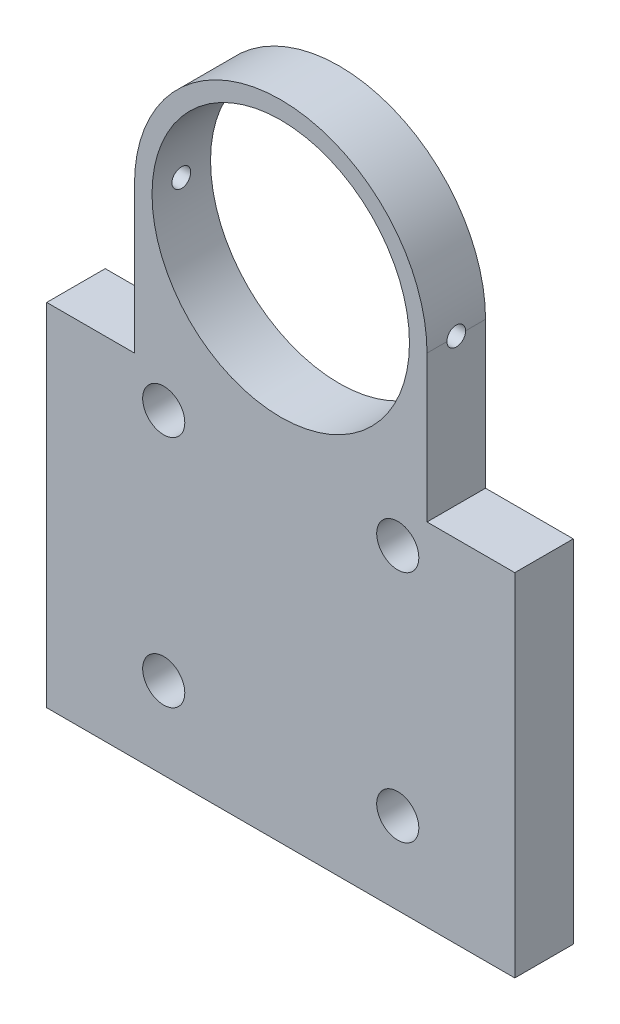
SolidWorks part; units mm, degrees
ref_plane "Plan de face" through (0, 0, 0) normal (0, 0, 1) x (1, 0, 0)
ref_plane "Plan de dessus" through (0, 0, 0) normal (0, 1, 0) x (1, 0, 0)
ref_plane "Plan de droite" through (0, 0, 0) normal (1, 0, 0) x (0, 0, -1)
sketch "Esquisse1" plane through (0, 0, 0) normal (0, 0, 1) x (1, 0, 0)
  line L1 (-21, 10.5789) -> (19, 10.5789)
  line L2 (-21, 10.5789) -> (-21, -19.4211)
  line L3 (-21, -19.4211) -> (19, -19.4211)
  line L4 (19, 10.5789) -> (19, -19.4211)
  dimension "D1" = 30
  dimension "D2" = 40
extrude "Boss.-Extru.1" add sketch "Esquisse1" along normal blind 5
sketch "Esquisse2" plane through (0, 0, 5) normal (0, 0, 1) x (1, 0, 0)
  line L0 (-1, 10.5789) -> (-1, 23.0789) construction
  line L1 (19, 10.5789) -> (-21, 10.5789) construction
  line L2 (-13.5, 23.0789) -> (-13.5, 10.5789)
  line L3 (11.5, 23.0789) -> (11.5, 10.5789)
  circle A0 centre (-1, 23.0789) radius 12.5
  dimension "D1" = 12.5
extrude "Boss.-Extru.2" add sketch "Esquisse2" against normal blind 5
sketch "Esquisse3" plane through (0, 0, 5) normal (0, 0, 1) x (1, 0, 0)
  line L0 (-13.5, 10.5789) -> (11.5, 10.5789) construction
  line L1 (-1, 10.5789) -> (-1, 35.5789) construction
  line L2 (-1, 10.5789) -> (-1, 7.5789) construction
  line L3 (-1, 7.5789) -> (-11, 7.5789) construction
  line L4 (-11, 7.5789) -> (-11, -12.4211) construction
  line L5 (-1, 7.5789) -> (9, 7.5789) construction
  line L6 (9, 7.5789) -> (9, -12.4211) construction
  arc A0 (11.5, 23.0789) -> (-13.5, 23.0789) centre (-1, 23.0789) ccw construction
  point P9 (-1, 23.0789)
  dimension "D1" = 20
  dimension "D2" = 10
  dimension "D3" = 10
  dimension "D4" = 20
  dimension "D5" = 3
  dimension "D6" = 25
hole_wizard "Trous de centrage Ø1.0mm1" positions "Esquisse3" profile "Esquisse5" hole size "Ø1.0" standard "ISO" end condition through all
sketch "Esquisse5" plane through (-1, 23.0789, 5) normal (1, 0, 0) x (0, -1, 0)
  line L0 (0, 0) -> (0, 5)
  line L1 (0, 5) -> (11, 5)
  line L2 (11, 5) -> (11, 0)
  line L5 (11, 0) -> (0, 0)
  line L11 (0, -6.35) -> (0, 107.95) construction
  dimension "Diamètre du perçage jusqu'au prochain" = 22
  dimension "Profondeur du perçage jusqu'au prochain" = 5
sketch "Esquisse8" plane through (0, 0, 5) normal (0, 0, 1) x (1, 0, 0)
  line L0 (-13.5, 10.5789) -> (11.5, 10.5789) construction
  line L1 (-1, 10.5789) -> (-1, 7.5789) construction
  line L2 (-1, 7.5789) -> (-11, 7.5789) construction
  line L3 (-11, 7.5789) -> (-11, -12.4211) construction
  line L4 (-1, 7.5789) -> (9, 7.5789) construction
  line L5 (9, 7.5789) -> (9, -12.4211) construction
  point P7 (-11, 7.5789)
  point P8 (-11, -12.4211)
  point P9 (9, 7.5789)
  point P10 (9, -12.4211)
  point P14 (-11, 7.5789)
  point P18 (-11, -12.4211)
  point P22 (9, -12.4211)
  point P26 (9, 7.5789)
  dimension "D1" = 3
  dimension "D2" = 10
  dimension "D3" = 10
  dimension "D4" = 20
  dimension "D5" = 20
hole_wizard "Dégagement M34" positions "Esquisse8" profile "Esquisse9" hole size "M3" standard "ISO" end condition through all
sketch "Esquisse9" plane through (9, 7.5789, 5) normal (1, 0, 0) x (0, -1, 0)
  line L0 (0, 0) -> (0, 5)
  line L1 (0, 5) -> (1.8, 5)
  line L2 (1.8, 5) -> (1.8, 0)
  line L5 (1.8, 0) -> (0, 0)
  line L11 (0, -6.35) -> (0, 107.95) construction
  dimension "Diamètre du perçage jusqu'au prochain" = 3.6
  dimension "Profondeur du perçage jusqu'au prochain" = 5
sketch "Esquisse10" plane through (11.5, 0, 0) normal (1, 0, 0) x (0, 0, -1)
  line L0 (-5, 23.0789) -> (0, 23.0789) construction
  point P6 (-2.5, 23.0789)
hole_wizard "Trou pour taraudage pour trou taraudé M23" positions "Esquisse10" profile "Esquisse11" hole size "M2" standard "ISO" end condition through all
sketch "Esquisse11" plane through (11.5, 23.0789, 2.5) normal (0, 1, 0) x (0, 0, -1)
  line L0 (0, 0) -> (0, 32.5)
  line L1 (0, 32.5) -> (0.8, 32.5)
  line L2 (0.8, 32.5) -> (0.8, 0)
  line L5 (0.8, 0) -> (0, 0)
  line L11 (0, -6.35) -> (0, 107.95) construction
  dimension "Diamètre du perçage jusqu'au prochain" = 1.6
  dimension "Profondeur du perçage jusqu'au prochain" = 32.5
